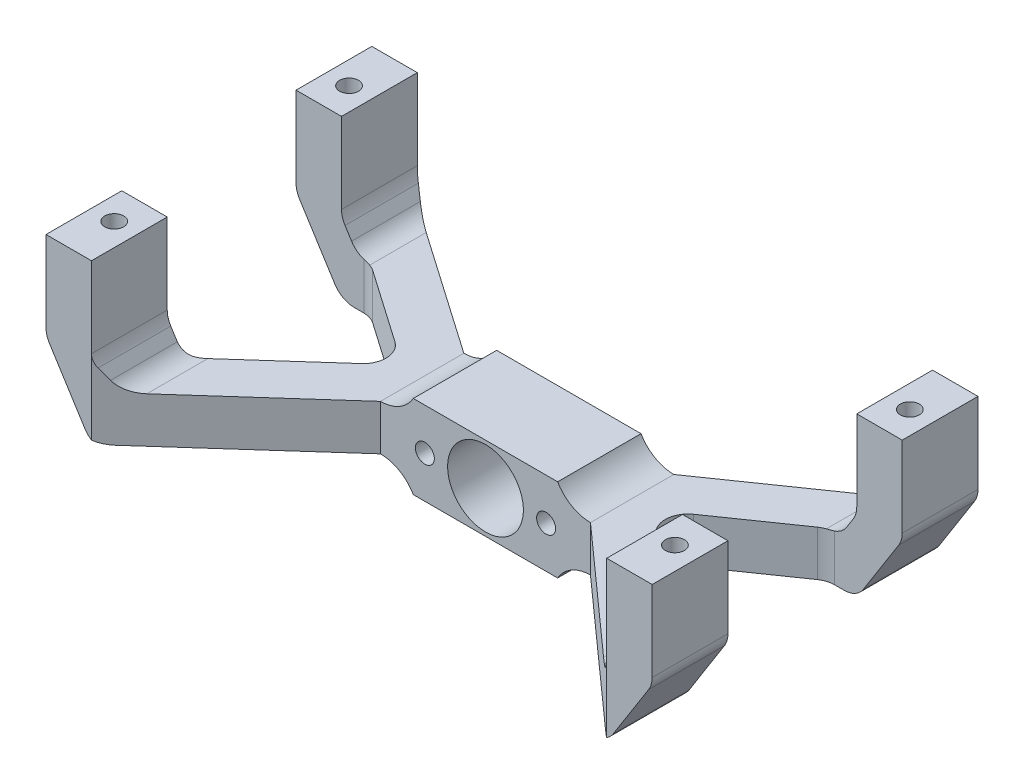
SolidWorks part; units mm, degrees
other "Markup1"
sketch "Sketch62" plane through (-128.5, -128.5, 146.8) normal (-0.0672, -0.6619, 0.7466) x (0.996, 0, 0.0896)
other "Markup2"
sketch "Sketch87" plane through (-128.5, 200.1498, -230) normal (-0.7911, 0.6051, -0.0891) x (-0.112, 0, 0.9937)
ref_plane "Front" through (0, 0, 0) normal (0, 0, 1) x (1, 0, 0)
ref_plane "Top" through (0, 0, 0) normal (0, 1, 0) x (1, 0, 0)
ref_plane "Right" through (0, 0, 0) normal (1, 0, 0) x (0, 0, -1)
sketch "Sketch1" plane through (0, 0, 0) normal (0, 0, 1) x (1, 0, 0)
  line L0 (-50.5181, 87.5) -> (0, 0) construction
  line L1 (101.0363, 0) -> (50.5181, 87.5)
  line L2 (50.5181, 87.5) -> (-50.5181, 87.5)
  line L3 (-50.5181, 87.5) -> (-101.0363, 0)
  line L4 (-101.0363, 0) -> (-50.5181, -87.5)
  line L5 (-50.5181, -87.5) -> (50.5181, -87.5)
  line L6 (50.5181, -87.5) -> (101.0363, 0)
  line L7 (0, 128.5) -> (-111.2843, 64.25) construction
  line L8 (-111.2843, 64.25) -> (-111.2843, -64.25) construction
  line L9 (-111.2843, -64.25) -> (0, -128.5) construction
  line L10 (0, -128.5) -> (111.2843, -64.25) construction
  line L11 (111.2843, -64.25) -> (111.2843, 64.25) construction
  line L12 (111.2843, 64.25) -> (0, 128.5) construction
  line L13 (0, 0) -> (50.5181, 87.5) construction
  line L14 (0, 0) -> (0, 200.1498) construction
  line L15 (-25, 93.5) -> (-25, 88.55) construction
  line L16 (-27.5, 91.1) -> (-22.5, 91.1)
  line L17 (-27.5, 91.1) -> (-27.5, 87.5)
  line L18 (-27.5, 87.5) -> (-22.5, 87.5)
  line L19 (-22.5, 91.1) -> (-22.5, 87.5)
  line L20 (-31, 93.5) -> (-19, 93.5)
  line L21 (-31, 93.5) -> (-31, 88.55)
  line L22 (-31, 88.55) -> (-19, 88.55)
  line L23 (-19, 93.5) -> (-19, 88.55)
  line L24 (48.2087, 83.5) -> (-48.2087, 83.5)
  line L25 (-48.2087, 83.5) -> (-96.4175, 0)
  line L26 (-96.4175, 0) -> (-48.2087, -83.5)
  line L27 (-48.2087, -83.5) -> (48.2087, -83.5)
  line L28 (48.2087, -83.5) -> (96.4175, 0)
  line L29 (96.4175, 0) -> (48.2087, 83.5)
  line L30 (-13, 105) -> (-13, 90) construction
  line L31 (-13, 105) -> (-0.0096, 97.5) construction
  line L32 (-11.2098, 101.4229) -> (-21.0467, 96.5)
  line L33 (-11.2098, 101.4229) -> (-7.6328, 103.2131)
  line L34 (-7.6328, 103.2131) -> (-9.4229, 106.7902)
  line L35 (-10.7973, 108.3389) -> (-23.318, 116.5991)
  line L36 (-22, 93.5) -> (-20, 93.5)
  line L37 (-22, 93.5) -> (-22, 91.5)
  line L38 (-22, 91.5) -> (-20, 91.5)
  line L39 (-20, 93.5) -> (-20, 91.5)
  line L40 (-30, 93.5) -> (-28, 93.5)
  line L41 (-30, 93.5) -> (-30, 91.5)
  line L42 (-30, 91.5) -> (-28, 91.5)
  line L43 (-28, 93.5) -> (-28, 91.5)
  line L44 (-26, 93.5) -> (-24, 93.5)
  line L45 (-26, 93.5) -> (-26, 91.5)
  line L46 (-26, 91.5) -> (-24, 91.5)
  line L47 (-24, 93.5) -> (-24, 91.5)
  line L48 (-10.7973, 108.3389) -> (-7.4584, 106.1361)
  line L49 (-7.4584, 106.1361) -> (-9.6611, 102.7973)
  line L50 (-12.9761, 110.6824) -> (-40, 97.9593)
  line L51 (-40, 97.9593) -> (-40, 93.5)
  line L52 (-40, 93.5) -> (-31, 93.5)
  line L53 (-14.7902, 108.5771) -> (-28.2041, 101.8639)
  line L54 (-40, 93.5) -> (-40, 82)
  line L55 (-40, 82) -> (-34, 72.5)
  line L56 (-34, 93.5) -> (-34, 82)
  line L57 (-34, 82) -> (-31.7895, 78.5)
  line L58 (-31.7895, 78.5) -> (-10.583, 78.5)
  line L59 (-34, 72.5) -> (-10.583, 72.5)
  line L60 (-19, 93.5) -> (-18.3926, 93.5)
  line L61 (-18.3926, 93.5) -> (-6.6883, 99.4573)
  line L62 (-6.6883, 99.4573) -> (0, 99.4573)
  line L63 (-12.9761, 110.6824) -> (-6.312, 107.0092)
  line L64 (-6.312, 107.0092) -> (0, 107.0092)
  line L65 (-6.4952, 79.25) -> (0, 75.5) construction
  line L66 (0, 75.5) -> (-8.2568, 75.5) construction
  line L67 (-9.5263, 81) -> (9.5263, 81)
  line L68 (-9.5263, 70) -> (9.5263, 70)
  line L69 (-37, 86.5) -> (-37, 97.0992) construction
  line L70 (-38.5, 93.5) -> (-35.5, 93.5) construction
  line L71 (-38.5, 93.5) -> (-38.5, 86.5) construction
  line L72 (-38.5, 86.5) -> (-35.5, 86.5) construction
  line L73 (-35.5, 93.5) -> (-35.5, 86.5) construction
  circle A0 centre (0, 0) radius 87.5 construction
  circle A1 centre (0, 0) radius 128.5 construction
  circle A2 centre (0, 128.5) radius 21 construction
  circle A3 centre (0, 128.5) radius 37.5 construction
  circle A4 centre (-13, 105) radius 1.5
  circle A5 centre (-13, 105) radius 15 construction
  circle A6 centre (-13, 105) radius 4
  arc A7 (-47.2558, 123.0415) -> (-49.9693, 122.4426) centre (-48.6061, 122.7128) ccw
  arc A8 (-47.2558, 123.0415) -> (-16.059, 109.9939) centre (-26.8516, 128.0083) ccw
  arc A9 (-49.9693, 122.4426) -> (-11.6134, 101.248) centre (-21.6463, 128.3951) ccw
  arc A10 (-14.5035, 143.6871) -> (-16.3789, 145.7376) centre (-15.4633, 144.6921) ccw
  arc A11 (-14.5035, 143.6871) -> (-10.2047, 110.1461) centre (0, 128.5) ccw
  arc A12 (-16.3789, 145.7376) -> (-15.556, 101.9232) centre (2.9376, 124.1854) ccw
  circle A13 centre (0, 75.5) radius 5
  circle A14 centre (0, 75.5) radius 3
  arc A15 (-9.5263, 81) -> (-9.5263, 70) centre (0, 75.5) ccw
  circle A16 centre (-6.4952, 79.25) radius 1.25 construction
  circle A18 centre (-6.4952, 79.25) radius 2.3 construction
  circle A19 centre (-6.4952, 71.75) radius 2.3 construction
  circle A20 centre (-6.4952, 71.75) radius 1.25 construction
  arc A21 (9.5263, 70) -> (9.5263, 81) centre (0, 75.5) ccw
  circle A22 centre (6.4952, 71.75) radius 1.25 construction
  circle A23 centre (6.4952, 79.25) radius 1.25 construction
  circle A24 centre (0, 0) radius 40.25 construction
  circle A25 centre (-8, 75.5) radius 1.75
  circle A26 centre (8, 75.5) radius 1.75
  point P29 (-25, 91.1)
  point P30 (-25, 93.5)
  point P73 (-25, 91.5)
  point P74 (-29, 91.5)
  point P75 (-21, 91.5)
  dimension "D1" = 175
  dimension "D2" = 257
  dimension "D3" = 42
  dimension "D4" = 75
  dimension "D5" = 3
  dimension "D14" = 30
  dimension "D15" = 8
  dimension "D26" = 6
  dimension "D27" = 10
  dimension "D28" = 22
  dimension "D30" = 2.5
  dimension "D31" = 4.6
  dimension "D40" = 80.5
  dimension "D41" = 3.5
  dimension "D6" = 3.6
  dimension "D7" = 6
  dimension "D8" = 12
  dimension "D9" = 5
  dimension "D10" = 4.95
  dimension "D11" = 25
  dimension "D13" = 60
  dimension "D16" = 15
  dimension "D17" = 2
  dimension "D18" = 8
  dimension "D19" = 2
  dimension "D20" = 5
  dimension "D21" = 13
  dimension "D22" = 17.5
  dimension "D23" = 60
  dimension "D24" = 19
  dimension "D25" = 40
  dimension "D29" = 7.5
  dimension "D32" = 30
  dimension "D33" = 11
  dimension "D34" = 8
  dimension "D35" = 6
  dimension "D36" = 3
  dimension "D37" = 7
  dimension "D38" = 11.5
  dimension "D39" = 6
  dimension "D42" = 16
  dimension "D12" = 4
sketch "Sketch9" plane through (0, 0, 0) normal (0, 0, 1) x (1, 0, 0)
  circle A0 centre (0, 75.5) radius 5 construction
  circle A1 centre (0, 75.5) radius 3 construction
  circle A2 centre (0, 75.5) radius 5
  circle A3 centre (0, 75.5) radius 3
sketch "Sketch10" plane through (0, 0, 0) normal (0, 0, 1) x (1, 0, 0)
  line L0 (-9.5263, 81) -> (9.5263, 81) construction
  line L1 (-9.5263, 70) -> (9.5263, 70) construction
  line L2 (-9.5263, 81) -> (9.5263, 81)
  line L3 (-9.5263, 70) -> (9.5263, 70)
  circle A0 centre (0, 75.5) radius 5 construction
  circle A1 centre (0, 75.5) radius 5
  arc A6 (9.5263, 70) -> (9.5263, 81) centre (0, 75.5) ccw construction
  arc A7 (-9.5263, 81) -> (-9.5263, 70) centre (0, 75.5) ccw construction
  arc A12 (9.5263, 70) -> (9.5263, 81) centre (0, 75.5) ccw
  arc A13 (-9.5263, 81) -> (-9.5263, 70) centre (0, 75.5) ccw
  circle A14 centre (-8, 75.5) radius 1.75 construction
  circle A15 centre (-8, 75.5) radius 1.75
  circle A16 centre (8, 75.5) radius 1.75 construction
  circle A17 centre (8, 75.5) radius 1.75
sketch "Sketch15" plane through (0, 0, 0) normal (0, 0, 1) x (1, 0, 0)
  line L0 (0, 0) -> (0, 200.1498) construction
  line L1 (0, 0) -> (0, 200.1498) construction
  line L2 (-9.5263, 70) -> (9.5263, 70) construction
  line L3 (-9.5263, 81) -> (9.5263, 81) construction
  line L4 (-40, 93.5) -> (-31, 93.5) construction
  line L5 (-34, 93.5) -> (-34, 82) construction
  line L6 (-34, 82) -> (-31.7895, 78.5) construction
  line L7 (-31.7895, 78.5) -> (-10.583, 78.5) construction
  line L8 (-40, 93.5) -> (-40, 82) construction
  line L9 (-40, 82) -> (-34, 72.5) construction
  line L10 (-34, 72.5) -> (-10.583, 72.5) construction
  line L11 (-9.5263, 70) -> (9.5263, 70)
  line L12 (-9.5263, 81) -> (9.5263, 81)
  line L13 (-40, 93.5) -> (-34, 93.5)
  line L14 (-34, 93.5) -> (-34, 82.8681)
  line L15 (-33.5365, 81.2661) -> (-32.6724, 79.898)
  line L16 (-30.136, 78.5) -> (-13.8564, 78.5)
  line L17 (-40, 93.5) -> (-40, 82.8681)
  line L18 (-39.5365, 81.2661) -> (-34.883, 73.898)
  line L19 (-32.3465, 72.5) -> (-13.8564, 72.5)
  line L20 (32.3465, 72.5) -> (13.8564, 72.5)
  line L21 (39.5365, 81.2661) -> (34.883, 73.898)
  line L22 (40, 93.5) -> (40, 82.8681)
  line L23 (30.136, 78.5) -> (13.8564, 78.5)
  line L24 (33.5365, 81.2661) -> (32.6724, 79.898)
  line L25 (34, 93.5) -> (34, 82.8681)
  line L26 (40, 93.5) -> (34, 93.5)
  arc A5 (-13.8564, 72.5) -> (-9.5263, 70) centre (-13.8564, 67.5) cw
  arc A6 (-13.8564, 78.5) -> (-9.5263, 81) centre (-13.8564, 83.5) ccw
  arc A7 (-34.883, 73.898) -> (-32.3465, 72.5) centre (-32.3465, 75.5) ccw
  arc A8 (-40, 82.8681) -> (-39.5365, 81.2661) centre (-37, 82.8681) ccw
  arc A9 (-32.6724, 79.898) -> (-30.136, 78.5) centre (-30.136, 81.5) ccw
  arc A10 (-34, 82.8681) -> (-33.5365, 81.2661) centre (-31, 82.8681) ccw
  arc A11 (34, 82.8681) -> (33.5365, 81.2661) centre (31, 82.8681) cw
  arc A12 (32.6724, 79.898) -> (30.136, 78.5) centre (30.136, 81.5) cw
  arc A13 (40, 82.8681) -> (39.5365, 81.2661) centre (37, 82.8681) cw
  arc A14 (34.883, 73.898) -> (32.3465, 72.5) centre (32.3465, 75.5) cw
  arc A15 (13.8564, 78.5) -> (9.5263, 81) centre (13.8564, 83.5) cw
  arc A16 (13.8564, 72.5) -> (9.5263, 70) centre (13.8564, 67.5) ccw
  circle A19 centre (0, 75.5) radius 5 construction
  circle A20 centre (0, 75.5) radius 5
  dimension "D1" = 5
  dimension "D2" = 3
extrude "Boss-Extrude7" add sketch "Sketch15" along normal mid plane 43 separate body
sketch "Sketch16" plane through (0, 70, 0) normal (0, -1, 0) x (1, 0, 0)
  line L0 (-9.5263, 3.5) -> (-13.8564, 3.5)
  line L1 (-13.8564, 3.5) -> (-34, 21.5)
  line L2 (-13.8564, 21.5) -> (-13.8564, -21.5) construction
  line L3 (-9.5263, -7.5) -> (-13.8564, -7.5)
  line L5 (-13.8564, -7.5) -> (-34, -21.5)
  line L6 (-34.883, -21.5) -> (-32.3465, -21.5) construction
  line L8 (0, 0) -> (0, 33.1336) construction
  line L9 (-9.5263, 3.5) -> (9.5263, 3.5)
  line L10 (-9.5263, -7.5) -> (9.5263, -7.5)
  line L11 (13.8564, -7.5) -> (34, -21.5)
  line L12 (9.5263, -7.5) -> (13.8564, -7.5)
  line L13 (13.8564, 3.5) -> (34, 21.5)
  line L14 (9.5263, 3.5) -> (13.8564, 3.5)
  line L15 (-34, 21.5) -> (34, 21.5)
  line L16 (34, -21.5) -> (-34, -21.5)
  line L17 (-9.5263, 21.5) -> (-9.5263, -21.5) construction
  point P2 (0, 0)
  point P5 (0, 0)
  point P12 (0, 0)
  point P17 (0, 0)
  point P18 (0, 0)
  point P23 (0, -7.5)
  point P24 (0, 3.5)
  point P29 (0, 0)
  dimension "D1" = 11
  dimension "D2" = 3.5
extrude "Cut-Extrude6" cut sketch "Sketch16" against normal through all
sketch "Sketch18" plane through (0, 70, 0) normal (0, -1, 0) x (1, 0, 0)
  line L7 (-17.8543, -0.974) -> (-36.3444, 15.5484)
  line L8 (-19.4301, 0.4341) -> (-30.96, 10.737)
  line L10 (-35.7707, -15.4239) -> (-17.2807, -2.5731)
  line L11 (-29.353, -10.9635) -> (-19.717, -4.2663)
  line L13 (-39.5365, 11.5) -> (-34.883, 11.5)
  line L14 (-40, 11.5) -> (-32.9589, 11.5)
  line L15 (-40, 11.5) -> (-40, -11.5)
  line L16 (-39.5365, -11.5) -> (-34.883, -11.5)
  line L17 (-40, -11.5) -> (-31.0651, -11.5)
  line L18 (-40, 21.5) -> (-40, -21.5) construction
  line L19 (0, 0) -> (0, 39.9552) construction
  line L20 (-9.5263, 0) -> (9.5263, 0) construction
  line L21 (40, -11.5) -> (31.0651, -11.5)
  line L22 (40, 11.5) -> (40, -11.5)
  line L23 (40, 11.5) -> (32.9589, 11.5)
  line L24 (29.353, -10.9635) -> (19.717, -4.2663)
  line L25 (19.4301, 0.4341) -> (30.96, 10.737)
  arc A0 (-29.353, -10.9635) -> (-31.0651, -11.5) centre (-31.0651, -8.5) cw
  arc A1 (-30.96, 10.737) -> (-32.9589, 11.5) centre (-32.9589, 8.5) ccw
  arc A2 (-19.717, -4.2663) -> (-19.4301, 0.4341) centre (-21.4291, -1.8029) ccw
  arc A3 (19.717, -4.2663) -> (19.4301, 0.4341) centre (21.4291, -1.8029) cw
  arc A4 (30.96, 10.737) -> (32.9589, 11.5) centre (32.9589, 8.5) cw
  arc A5 (29.353, -10.9635) -> (31.0651, -11.5) centre (31.0651, -8.5) ccw
  dimension "D5" = 3
  dimension "D1" = 6
  dimension "D2" = 6
  dimension "D3" = 10
  dimension "D4" = 10
extrude "Cut-Extrude7" cut sketch "Sketch18" against normal through all
hole_wizard "M3 Tapped Hole1" positions "3DSketch1" profile "Sketch88" tap size "M3" standard "ISO" end condition through all
sketch3d "3DSketch1"
  circle A0 centre (-8, 75.5, 0) radius 1.75 construction
  circle A1 centre (8, 75.5, 0) radius 1.75 construction
  point P3 (-8, 75.5, 3.5)
  point P5 (8, 75.5, 3.5)
  point P8 (0, 0, 0)
  point P9 (-8.4877, 75.0112, 3.5)
  point P10 (0, 0, 0)
  point P11 (-8.2238, 74.8833, 3.5)
  point P14 (-8, 75.5, 1.75)
  point P15 (0, 0, 0)
  point P18 (8, 75.5, -1.75)
sketch "Sketch88" plane through (-8, 75.5, 3.5) normal (1, 0, 0) x (0, -1, 0)
  line L0 (0, 0) -> (0, 25)
  line L1 (0, 25) -> (1.25, 25)
  line L2 (1.25, 25) -> (1.25, 0)
  line L5 (1.25, 0) -> (0, 0)
  line L11 (0, -6.35) -> (0, 107.95) construction
  dimension "Thru Tap Drill Dia." = 2.5
  dimension "Thru Tap Drill Depth" = 25
cosmetic thread "Hole Thread59" parameters "D2"=3
cosmetic thread "Hole Thread60" parameters "D2"=3
sketch "Sketch89" plane through (0, 93.5, 0) normal (0, 1, 0) x (1, 0, 0)
  line L1 (37, -15.5) -> (-37, -15.5) construction
  line L2 (37, -15.5) -> (37, 15.5) construction
  line L3 (37, 15.5) -> (-37, 15.5) construction
  line L4 (-37, -15.5) -> (-37, 15.5) construction
  line L5 (37, -15.5) -> (-37, 15.5) construction
  line L6 (37, 15.5) -> (-37, -15.5) construction
  point P0 (0, 0)
  dimension "D1" = 74
  dimension "D2" = 31
hole_wizard "M3 Tapped Hole2" positions "3DSketch2" profile "Sketch90" tap size "M3" standard "ISO"
sketch3d "3DSketch2"
  point P0 (-37, 93.5, -15.5)
  point P3 (37, 93.5, -15.5)
  point P6 (37, 93.5, 15.5)
  point P9 (-37, 93.5, 15.5)
sketch "Sketch90" plane through (-37, 93.5, -15.5) normal (1, 0, 0) x (0, 0, 1)
  line L0 (0, 0) -> (0, 8.2511)
  line L1 (0, 8.2511) -> (1.25, 7.5)
  line L2 (1.25, 7.5) -> (1.25, 0)
  line L5 (1.25, 0) -> (0, 0)
  line L10 (0, 8.2511) -> (-1.25, 7.5) construction
  line L11 (0, -6.35) -> (0, 107.95) construction
  dimension "Tap Drill Dia." = 2.5
  dimension "Tap Drill Depth" = 7.5
  dimension "Drill Angle" = 118
cosmetic thread "Hole Thread61" parameters "D1"=6, "D2"=3
cosmetic thread "Hole Thread62" parameters "D1"=6, "D2"=3
cosmetic thread "Hole Thread63" parameters "D1"=6, "D2"=3
cosmetic thread "Hole Thread64" parameters "D1"=6, "D2"=3
equation "\"D39@Sketch1\"=\"D35@Sketch1\""
